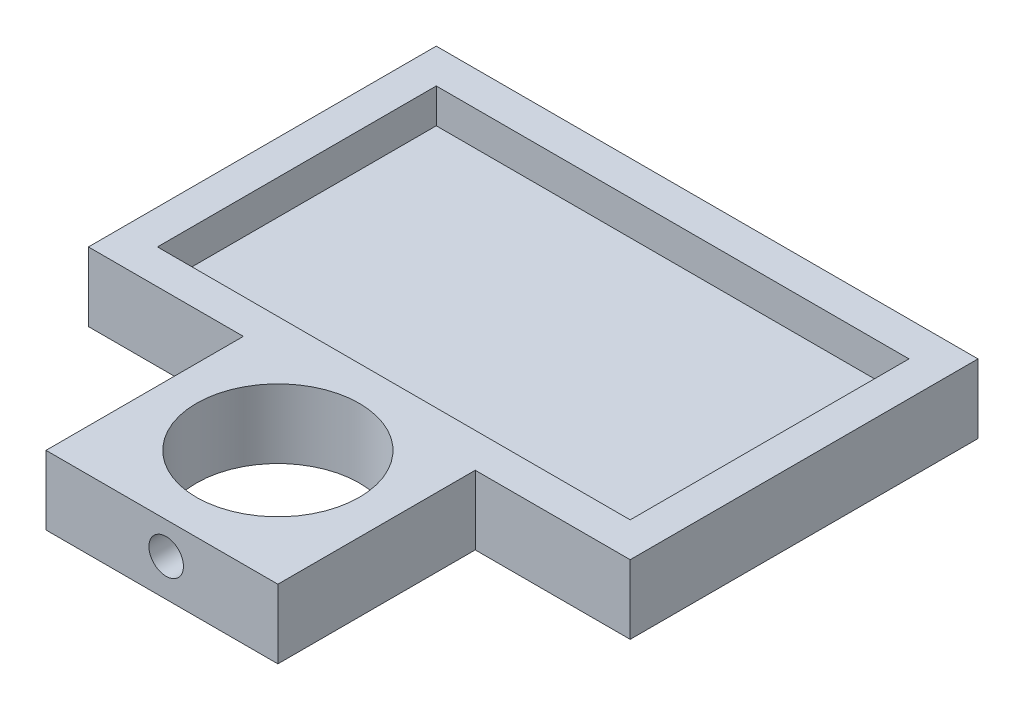
SolidWorks part; units mm, degrees
ref_plane "Front Plane" through (0, 0, 0) normal (0, 0, 1) x (1, 0, 0)
ref_plane "Top Plane" through (0, 0, 0) normal (0, 1, 0) x (1, 0, 0)
ref_plane "Right Plane" through (0, 0, 0) normal (1, 0, 0) x (0, 0, -1)
sketch "Sketch2" plane through (0, 0, 0) normal (0, 1, 0) x (1, 0, 0)
  line L1 (-81.5703, 45.402) -> (-3.0703, 45.402)
  line L2 (-81.5703, 45.402) -> (-81.5703, -4.998)
  line L3 (-81.5703, -4.998) -> (-3.0703, -4.998)
  line L4 (-3.0703, 45.402) -> (-3.0703, -4.998)
  dimension "D1" = 78.5
  dimension "D2" = 50.4
extrude "Boss-Extrude2" add sketch "Sketch2" along normal blind 10
sketch "Sketch3" plane through (0, 10, 0) normal (0, 1, 0) x (1, 0, 0)
  line L0 (-3.0703, 45.402) -> (-81.5703, 45.402) construction
  line L1 (-76.5703, 40.402) -> (-8.0703, 40.402)
  line L2 (-76.5703, 40.402) -> (-76.5703, 0.002)
  line L3 (-76.5703, 0.002) -> (-8.0703, 0.002)
  line L4 (-8.0703, 40.402) -> (-8.0703, 0.002)
  line L5 (-81.5703, -4.998) -> (-3.0703, -4.998) construction
  line L6 (-3.0703, -4.998) -> (-3.0703, 45.402) construction
  line L8 (-81.5703, 45.402) -> (-81.5703, -4.998) construction
  dimension "D1" = 5
  dimension "D3" = 5
  dimension "D4" = 5
  dimension "D2" = 5
extrude "Cut-Extrude1" cut sketch "Sketch3" against normal blind 5
sketch "Sketch6" plane through (0, 10, 0) normal (0, 1, 0) x (1, 0, 0)
  line L1 (-76.5703, 0.002) -> (-8.0703, 0.002) construction
  line L3 (-59.1203, 0.002) -> (-25.5203, 0.002)
  line L4 (-59.1203, 0.002) -> (-59.1203, -33.598)
  line L5 (-59.1203, -33.598) -> (-25.5203, -33.598)
  line L6 (-25.5203, 0.002) -> (-25.5203, -33.598)
  line L7 (-8.0703, 0.002) -> (-8.0703, 40.402) construction
  circle A1 centre (-42.3203, -16.798) radius 11.8
  dimension "D1" = 23.6
  dimension "D2" = 34.25
  dimension "D3" = 16.8
  dimension "D4" = 16.8
  dimension "D5" = 16.8
extrude "Boss-Extrude4" add sketch "Sketch6" against normal up to surface (10 mm away) up to face at (-42.3203, 0, -20.202)
hole_wizard "M6x1.0 Tapped Hole5" positions "3DSketch7" profile "Sketch7" tap size "M6x1.0" standard "ANSI Metric"
sketch3d "3DSketch7"
  point P0 (-41.7045, 5.3933, 33.598)
sketch "Sketch7" plane through (-41.7045, 5.3933, 33.598) normal (1, 0, 0) x (0, -1, 0)
  line L0 (0, 0) -> (0, 5.0161)
  line L1 (0, 5.0161) -> (2.5, 5.0161)
  line L2 (2.5, 5.0161) -> (2.5, 0)
  line L5 (2.5, 0) -> (0, 0)
  line L11 (0, -6.35) -> (0, 107.95) construction
  dimension "Thread Major Dia." = 5
  dimension "Thru Tap Drill Depth" = 5.0161
equation "\"w1\"= ( 21.68 + 21.52 ) / 2"
equation "\"w2\"= ( 19.35 + 19.57 ) / 2"
equation "\"w3\"= 17.03"
equation "\"w4\"= ( 15.09 + 15.18 ) / 2"
equation "\"w5\"= 13.2"
equation "\"w6\"= ( 11.13 + 11.42 ) / 2"
equation "\"w7\"= 9.3"
equation "\"mount_height\" = 20"
equation "\"mount_thickness\"= 5"
equation "\"camera_depth\"= 40.4"
equation "\"holder_height\"= 5"
equation "\"camera_width\"= 68.5"
equation "\"D1@Sketch2\"=\"mount_thickness\"*2+\"camera_width\""
equation "\"D2@Sketch2\"=\"mount_thickness\"*2+\"camera_depth\""
equation "\"D1@Boss-Extrude2\"=\"holder_height\"*2"
equation "\"D3@Sketch3\"=\"D1@Sketch3\""
equation "\"D4@Sketch3\"=\"mount_thickness\""
equation "\"D2@Sketch3\"=\"mount_thickness\""
equation "\"D1@Cut-Extrude1\"=\"holder_height\""
equation "\"tolerance\"= 2"
equation "\"D1@Sketch6\"=\"w1\"+\"tolerance\""
equation "\"D2@Sketch6\"=\"camera_width\"/2"
equation "\"D3@Sketch6\"=\"D1@Sketch6\"/2+\"mount_thickness\""
equation "\"D4@Sketch6\"=\"D3@Sketch6\""
equation "\"D5@Sketch6\"=\"D3@Sketch6\""
